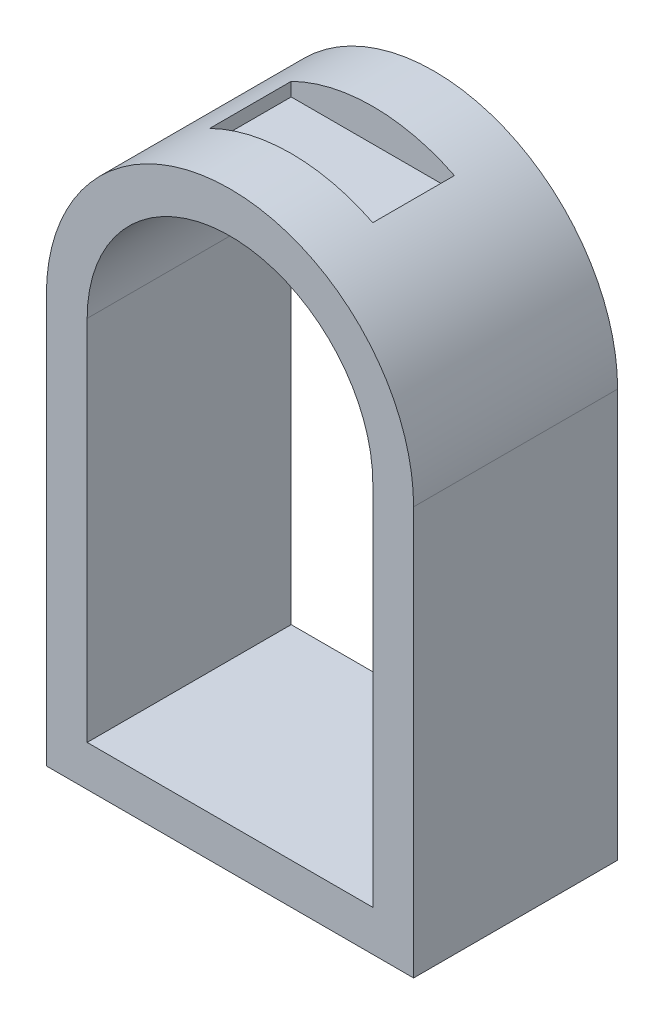
SolidWorks part; units mm, degrees
ref_plane "Front Plane" through (0, 0, 0) normal (0, 0, 1) x (1, 0, 0)
ref_plane "Top Plane" through (0, 0, 0) normal (0, 1, 0) x (1, 0, 0)
ref_plane "Right Plane" through (0, 0, 0) normal (1, 0, 0) x (0, 0, -1)
sketch "Sketch1" plane through (0, 0, 0) normal (0, 0, 1) x (1, 0, 0)
  line L0 (-177.8, 0) -> (0, 0)
  line L1 (0, 0) -> (0, 228.6)
  line L3 (-177.8, 228.6) -> (-177.8, 0)
  arc A0 (-177.8, 228.6) -> (0, 228.6) centre (-88.9, 228.6) cw
  point P6 (0, 0)
  point P7 (0, 0)
  dimension "D1" = 228.6
  dimension "D2" = 177.8
extrude "Extrude-Thin1" add sketch "Sketch1" along normal blind 127 thin contours L1 A0 L3 L0
ref_plane "Plane1" through (0, 342.9, 0) normal (0, 1, 0) x (1, 0, 0)
sketch "Sketch4" plane through (0, 342.9, 0) normal (0, 1, 0) x (1, 0, 0)
  line L0 (-203.2, -63.5) -> (-139.7, -63.5) construction
  line L1 (-139.7, -88.9) -> (-38.1, -88.9)
  line L2 (-139.7, -88.9) -> (-139.7, -38.1)
  line L3 (-139.7, -38.1) -> (-38.1, -38.1)
  line L4 (-38.1, -88.9) -> (-38.1, -38.1)
  line L5 (-139.7, -88.9) -> (-38.1, -38.1) construction
  line L6 (-139.7, -38.1) -> (-38.1, -88.9) construction
  line L7 (-203.2, -127) -> (-203.2, 0) construction
  line L8 (-88.9, 0) -> (-88.9, -38.1) construction
  line L9 (25.4, 0) -> (-203.2, 0) construction
  point P0 (-88.9, -63.5)
  dimension "D1" = 101.6
  dimension "D2" = 50.8
extrude "Cut-Extrude1" cut sketch "Sketch4" against normal blind 20.32
